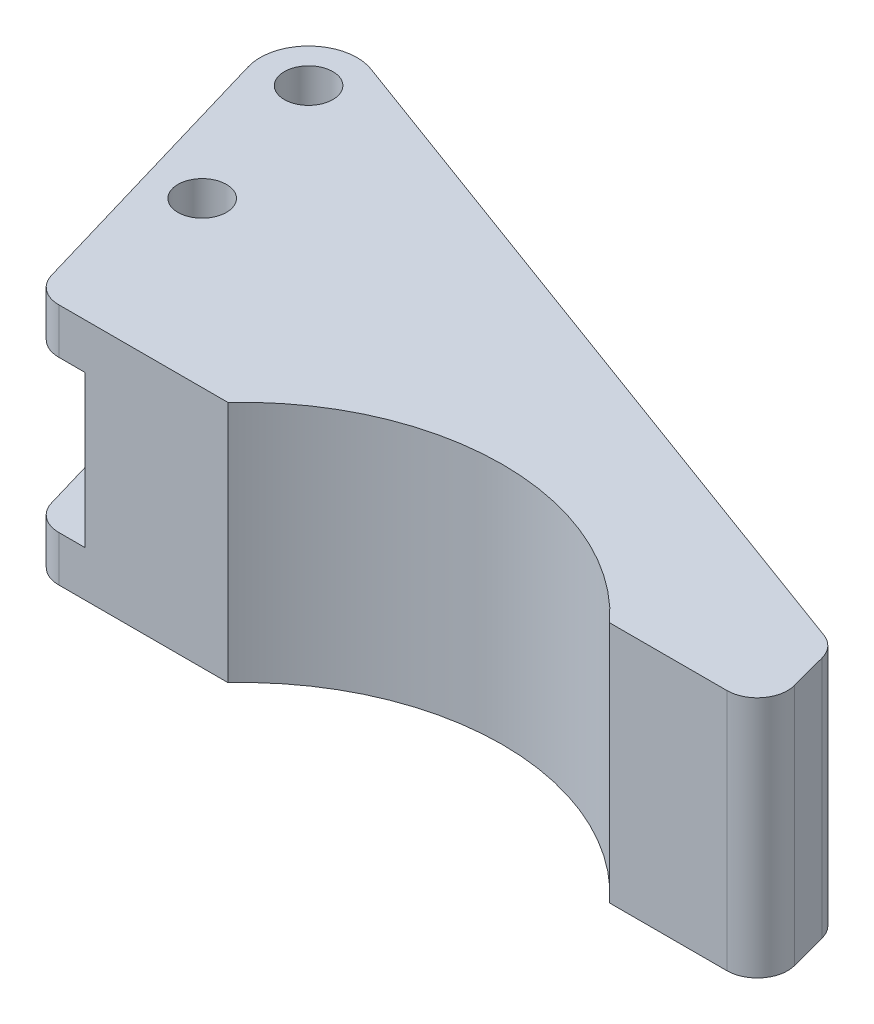
SolidWorks part; units mm, degrees
ref_plane "前视基准面" through (0, 0, 0) normal (0, 0, 1) x (1, 0, 0)
ref_plane "上视基准面" through (0, 0, 0) normal (0, 1, 0) x (1, 0, 0)
ref_plane "右视基准面" through (0, 0, 0) normal (1, 0, 0) x (0, 0, -1)
sketch "草图1" plane through (0, 0, 0) normal (0, 1, 0) x (1, 0, 0)
  line L0 (-7.6735, -2.2622) -> (5.8941, -48.2839)
  line L1 (10.69, -51.87) -> (38.5852, -51.87)
  line L2 (101.4948, -51.87) -> (120.83, -51.87)
  line L3 (125.6618, -45.5841) -> (124.0118, -39.3841)
  line L4 (120.9071, -35.9778) -> (2.7633, 7.5076)
  circle A0 centre (0, 0) radius 4
  arc A1 (-7.6735, -2.2622) -> (2.7633, 7.5076) centre (0, 0) cw
  arc A2 (38.5852, -51.87) -> (101.4948, -51.87) centre (70.04, -80.88) cw
  arc A3 (120.83, -51.87) -> (125.6618, -45.5841) centre (120.83, -46.87) ccw
  arc A4 (124.0118, -39.3841) -> (120.9071, -35.9778) centre (119.18, -40.67) ccw
  arc A5 (5.8941, -48.2839) -> (10.69, -51.87) centre (10.69, -46.87) ccw
  circle A6 centre (7.33, -24.87) radius 4
  dimension "D1" = 8
  dimension "D2" = 5
  dimension "D4" = 5
  dimension "D5" = 5
  dimension "D8" = 42.79
  dimension "D11" = 8
  dimension "D16" = 8
  dimension "D3" = 110.14
  dimension "D6" = 6.2
  dimension "D7" = 1.65
  dimension "D9" = 59.35
  dimension "D10" = 29.01
  dimension "D12" = 7.33
  dimension "D13" = 3.36
  dimension "D14" = 27
  dimension "D15" = 24.87
extrude "凸台-拉伸1" add sketch "草图1" along normal mid plane 40
sketch "草图2" plane through (0, 0, 0) normal (0, 0, 1) x (1, 0, 0)
  line L0 (-8, 20) -> (-8, -20) construction
  line L1 (-8, 12.5) -> (15, 12.5)
  line L2 (-8, 12.5) -> (-8, -12.5)
  line L3 (-8, -12.5) -> (15, -12.5)
  line L4 (15, 12.5) -> (15, -12.5)
  point P4 (15, 0)
  dimension "D1" = 23
  dimension "D2" = 25
extrude "切除-拉伸1" cut sketch "草图2" against normal through all both and the other way through all
